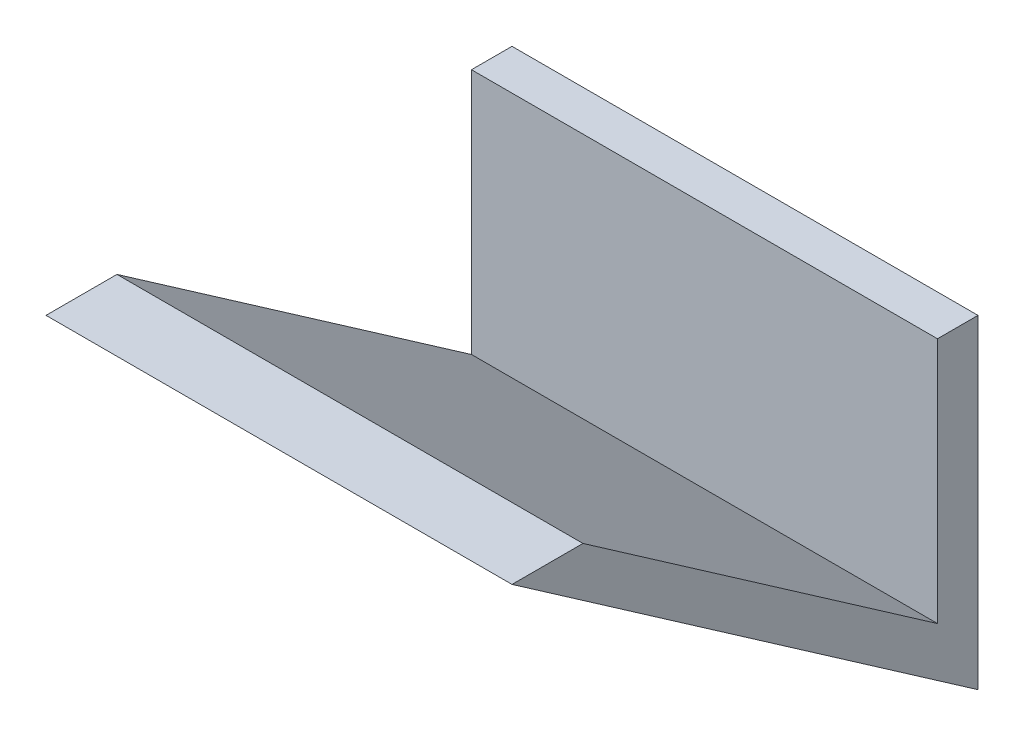
SolidWorks part; units mm, degrees
ref_plane "Front Plane" through (0, 0, 0) normal (0, 0, 1) x (1, 0, 0)
ref_plane "Top Plane" through (0, 0, 0) normal (0, 1, 0) x (1, 0, 0)
ref_plane "Right Plane" through (0, 0, 0) normal (1, 0, 0) x (0, 0, -1)
sketch "Sketch3" plane through (0, 0, 0) normal (0, 0, 1) x (1, 0, 0)
  line L1 (-30.7528, 27.264) -> (26.7472, 27.264)
  line L2 (-30.7528, 27.264) -> (-30.7528, -12.736)
  line L3 (-30.7528, -12.736) -> (26.7472, -12.736)
  line L4 (26.7472, 27.264) -> (26.7472, -12.736)
  dimension "D1" = 57.5
  dimension "D2" = 40
extrude "Boss-Extrude1" add sketch "Sketch3" along normal blind 57.5
sketch "Sketch7" plane through (26.7472, 0, 0) normal (1, 0, 0) x (0, 0, -1)
  line L0 (-57.5, 27.264) -> (0, -12.736)
  line L1 (0, 55) -> (0, -55) construction
  line L2 (-57.5, -12.736) -> (0, -12.736) construction
  line L3 (0, -12.736) -> (-57.5, -12.736)
  line L4 (-57.5, -12.736) -> (-57.5, 27.264) construction
  line L5 (-57.5, -12.736) -> (-57.5, 27.264)
extrude "Cut-Extrude1" cut sketch "Sketch7" against normal through all
sketch "Sketch8" plane through (26.7472, 0, 0) normal (1, 0, 0) x (0, 0, -1)
  line L0 (-5, 27.264) -> (-5, -3.1669)
  line L1 (-57.5, 27.264) -> (0, 27.264) construction
  line L2 (-5, -3.1669) -> (-48.7444, 27.264)
  line L3 (-48.7444, 27.264) -> (-5, 27.264)
  line L4 (0, 22) -> (0, -22) construction
  line L6 (0, -12.736) -> (-57.5, 27.264) construction
  dimension "D1" = 5
  dimension "D2" = 5
extrude "Cut-Extrude2" cut sketch "Sketch8" against normal through all
